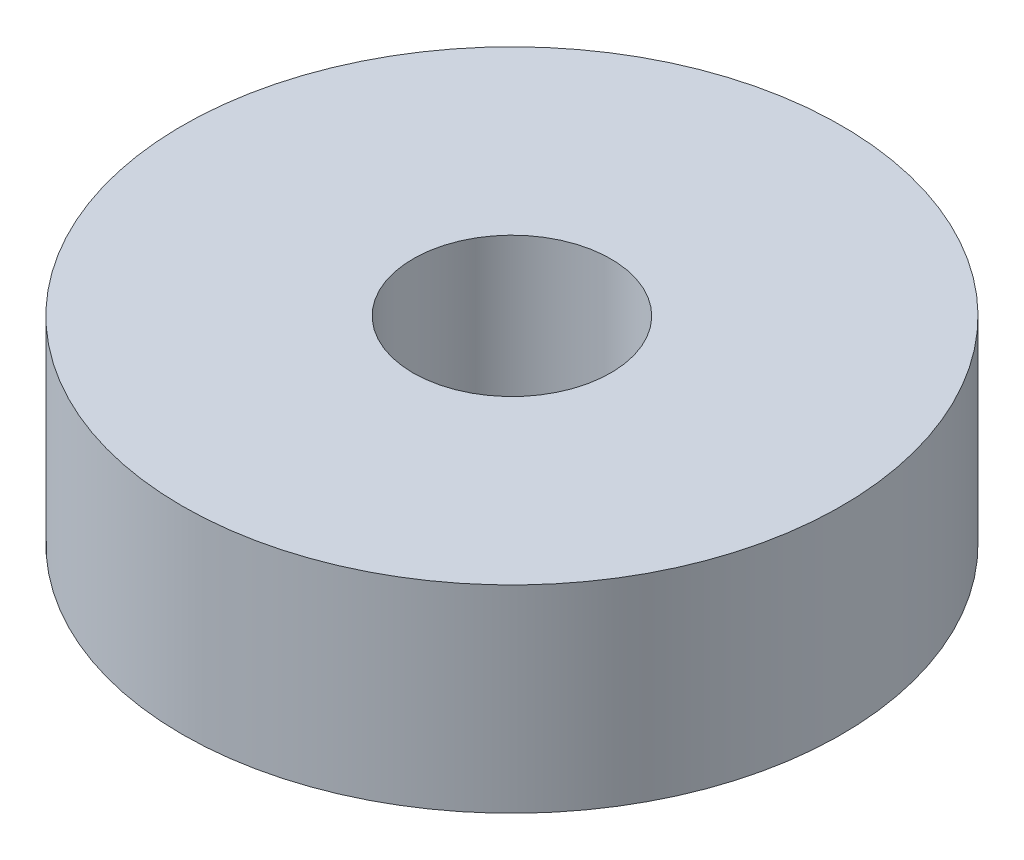
SolidWorks part; units mm, degrees
ref_plane "前视基准面" through (0, 0, 0) normal (0, 0, 1) x (1, 0, 0)
ref_plane "上视基准面" through (0, 0, 0) normal (0, 1, 0) x (1, 0, 0)
ref_plane "右视基准面" through (0, 0, 0) normal (1, 0, 0) x (0, 0, -1)
sketch "草图1" plane through (0, 0, 0) normal (0, 1, 0) x (1, 0, 0)
  circle A0 centre (0, 0) radius 1.5
  circle A1 centre (0, 0) radius 5
  dimension "D1" = 3
  dimension "D2" = 10
extrude "凸台-拉伸1" add sketch "草图1" along normal blind 3
